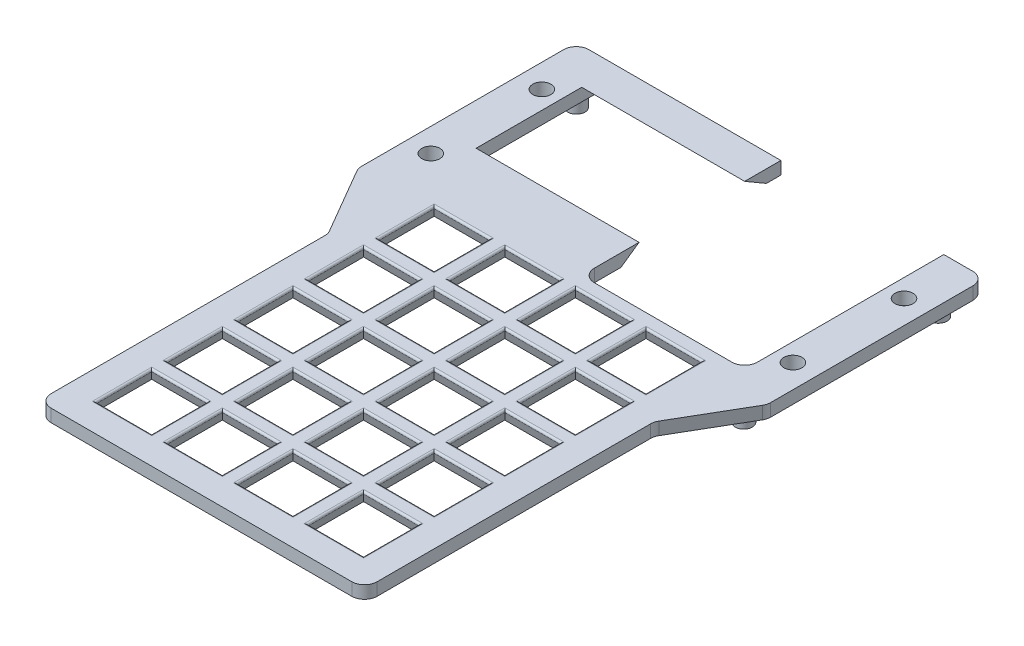
SolidWorks part; units mm, degrees
ref_plane "Front Plane" through (0, 0, 0) normal (0, 0, 1) x (1, 0, 0)
ref_plane "Top Plane" through (0, 0, 0) normal (0, 1, 0) x (1, 0, 0)
ref_plane "Right Plane" through (0, 0, 0) normal (1, 0, 0) x (0, 0, -1)
sketch "Sketch1" plane through (0, 0, 0) normal (0, 1, 0) x (1, 0, 0)
  line L0 (-57.5973, -8.4441) -> (-46.0973, -28.1941)
  line L1 (-46.0973, 51.8059) -> (43.9027, 51.8059)
  line L2 (-46.0973, 51.8059) -> (-46.0973, -108.1941)
  line L3 (-46.0973, -108.1941) -> (43.9027, -108.1941)
  line L4 (43.9027, 51.8059) -> (43.9027, -108.1941)
  line L5 (-57.5973, 51.8059) -> (55.4027, 51.8059)
  line L6 (-57.5973, 51.8059) -> (-57.5973, -8.4441)
  line L7 (-57.5973, -8.4441) -> (55.4027, -8.4441)
  line L8 (55.4027, 51.8059) -> (55.4027, -8.4441)
  line L9 (-57.5973, -8.4441) -> (-46.0973, -8.4441)
  line L10 (-46.0973, -8.4441) -> (-46.0973, -28.1941)
  line L11 (43.9027, -28.1941) -> (43.9027, -8.4441)
  line L12 (43.9027, -8.4441) -> (55.4027, -8.4441)
  line L13 (43.9027, -28.1941) -> (55.4027, -8.4441)
  point P12 (-1.0973, 51.8059)
  point P13 (-1.0973, 51.8059)
  dimension "D1" = 90
  dimension "D2" = 160
  dimension "D3" = 99.75
  dimension "D4" = 113
extrude "Boss-Extrude1" add sketch "Sketch1" along normal blind 3.5 contours L8 L5 L4 L7 | L2 L7 L4 L1 | L6 L7 L2 L5 | L7 L0 L2 | L7 L2 L3 L4 | L4 L13 L7
sketch "Sketch2" plane through (0, 0, 0) normal (0, -1, 0) x (1, 0, 0)
  line L2 (-46.0973, 28.1941) -> (-46.0973, 108.1941) construction
  line L3 (-57.5973, -51.8059) -> (55.4027, -51.8059) construction
  line L4 (-57.5973, -51.8059) -> (-57.5973, 8.4441) construction
  line L5 (55.4027, -51.8059) -> (55.4027, 8.4441) construction
  circle A2 centre (-51.0973, -45.3059) radius 2.4
  circle A3 centre (48.9027, -45.3059) radius 2.4
  circle A4 centre (-31.8473, -5.1309) radius 2.4
  circle A5 centre (-21.8473, -5.1309) radius 2.4
  circle A6 centre (47.4027, 6.9441) radius 2.35
  circle A7 centre (-49.5973, 6.9441) radius 2.35
  point P0 (0, 0)
  dimension "D5" = 4.8
  dimension "D6" = 4.8
  dimension "D12" = 4.8
  dimension "D13" = 4.8
  dimension "D16" = 21.25
  dimension "D18" = 4.7
  dimension "D19" = 4.7
  dimension "D2" = 8
  dimension "D3" = 21.25
  dimension "D4" = 8
  dimension "D7" = 6.5
  dimension "D8" = 6.5
  dimension "D9" = 6.5
  dimension "D10" = 6.5
  dimension "D11" = 10
  dimension "D14" = 14.25
  dimension "D15" = 46.675
extrude "Boss-Extrude2" add sketch "Sketch2" along normal blind 5.5
sketch "Sketch3" plane through (0, 0, 0) normal (0, -1, 0) x (1, 0, 0)
  line L0 (-57.5973, -51.8059) -> (-57.5973, 8.4441) construction
  line L1 (-57.5973, -51.8059) -> (55.4027, -51.8059) construction
  line L2 (55.4027, -51.8059) -> (55.4027, 8.4441) construction
  line L12 (-46.0973, -12.6458) -> (43.9027, -12.6458)
  line L13 (-46.0973, -12.6458) -> (-46.0973, -41.8059)
  line L14 (-46.0973, -41.8059) -> (43.9027, -41.8059)
  line L15 (43.9027, -12.6458) -> (43.9027, -41.8059)
  line L16 (43.9027, -12.6458) -> (-1.0973, -12.6458)
  line L17 (43.9027, -12.6458) -> (43.9027, 3.1941)
  line L18 (43.9027, 3.1941) -> (-1.0973, 3.1941)
  line L19 (-1.0973, -12.6458) -> (-1.0973, 3.1941)
  line L20 (-1.0973, -41.8059) -> (43.9027, -41.8059)
  line L21 (-1.0973, -41.8059) -> (-1.0973, -51.8059)
  line L22 (-1.0973, -51.8059) -> (43.9027, -51.8059)
  line L23 (43.9027, -41.8059) -> (43.9027, -51.8059)
  circle A0 centre (-51.0973, -35.8059) radius 2.5
  circle A1 centre (48.9027, -35.8059) radius 2.5
  circle A2 centre (-51.0973, -5.1309) radius 2.5
  circle A3 centre (48.9027, -5.1309) radius 2.5
  circle A5 centre (-21.8473, -5.1309) radius 2.4
  circle A6 centre (-21.8473, -5.1309) radius 2.4
  point P21 (0, 0)
  point P30 (-1.0973, -51.8059)
  point P31 (-1.0973, -41.8059)
  dimension "D3" = 5
  dimension "D9" = 5
  dimension "D10" = 5
  dimension "D11" = 5
  dimension "D1" = 6.5
  dimension "D2" = 16
  dimension "D4" = 6.5
  dimension "D5" = 16
  dimension "D6" = 6.5
  dimension "D7" = 6.5
  dimension "D13" = 45
  dimension "D18" = 90
  dimension "D19" = 45
  dimension "D16" = 0
extrude "Cut-Extrude1" cut sketch "Sketch3" against normal blind 5 contours L21 L20 L23 L22 | L13 L12 L15 L14 | L17 L16 L19 L18 | A0 | A2 | A3 | A1
sketch "Sketch4" plane through (0, 3.5, 0) normal (0, -1, 0) x (1, 0, 0)
  line L0 (-46.0973, 108.1941) -> (43.9027, 108.1941) construction
  line L1 (-37.8473, 100.1941) -> (-22.8473, 100.1941)
  line L2 (-37.8473, 100.1941) -> (-37.8473, 85.1941)
  line L3 (-37.8473, 85.1941) -> (-22.8473, 85.1941)
  line L4 (-22.8473, 100.1941) -> (-22.8473, 85.1941)
  line L5 (-46.0973, 28.1941) -> (-46.0973, 108.1941) construction
  line L6 (-18.3473, 85.1941) -> (-3.3473, 85.1941)
  line L7 (-18.3473, 85.1941) -> (-18.3473, 100.1941)
  line L8 (-18.3473, 100.1941) -> (-3.3473, 100.1941)
  line L9 (-3.3473, 85.1941) -> (-3.3473, 100.1941)
  line L10 (1.1527, 100.1941) -> (16.1527, 100.1941)
  line L11 (1.1527, 100.1941) -> (1.1527, 85.1941)
  line L12 (1.1527, 85.1941) -> (16.1527, 85.1941)
  line L13 (16.1527, 100.1941) -> (16.1527, 85.1941)
  line L14 (20.6527, 100.1941) -> (35.6527, 100.1941)
  line L15 (20.6527, 100.1941) -> (20.6527, 85.1941)
  line L16 (20.6527, 85.1941) -> (35.6527, 85.1941)
  line L17 (35.6527, 100.1941) -> (35.6527, 85.1941)
  line L19 (-18.3473, 41.6941) -> (-3.3473, 41.6941)
  line L20 (-18.3473, 41.6941) -> (-18.3473, 26.6941)
  line L21 (-37.8473, 80.6941) -> (-22.8473, 80.6941)
  line L22 (-37.8473, 80.6941) -> (-37.8473, 65.6941)
  line L23 (-37.8473, 65.6941) -> (-22.8473, 65.6941)
  line L24 (-22.8473, 80.6941) -> (-22.8473, 65.6941)
  line L25 (-18.3473, 80.6941) -> (-3.3473, 80.6941)
  line L26 (-18.3473, 80.6941) -> (-18.3473, 65.6941)
  line L27 (-18.3473, 65.6941) -> (-3.3473, 65.6941)
  line L28 (-3.3473, 80.6941) -> (-3.3473, 65.6941)
  line L29 (1.1527, 80.6941) -> (16.1527, 80.6941)
  line L30 (1.1527, 80.6941) -> (1.1527, 65.6941)
  line L31 (1.1527, 65.6941) -> (16.1527, 65.6941)
  line L32 (16.1527, 80.6941) -> (16.1527, 65.6941)
  line L33 (20.6527, 80.6941) -> (35.6527, 80.6941)
  line L34 (20.6527, 80.6941) -> (20.6527, 65.6941)
  line L35 (20.6527, 65.6941) -> (35.6527, 65.6941)
  line L36 (35.6527, 80.6941) -> (35.6527, 65.6941)
  line L37 (-37.8473, 61.1941) -> (-22.8473, 61.1941)
  line L38 (-37.8473, 61.1941) -> (-37.8473, 46.1941)
  line L39 (-37.8473, 46.1941) -> (-22.8473, 46.1941)
  line L40 (-22.8473, 61.1941) -> (-22.8473, 46.1941)
  line L41 (-18.3473, 61.1941) -> (-3.3473, 61.1941)
  line L42 (-18.3473, 61.1941) -> (-18.3473, 46.1941)
  line L43 (-18.3473, 46.1941) -> (-3.3473, 46.1941)
  line L44 (-3.3473, 61.1941) -> (-3.3473, 46.1941)
  line L45 (1.1527, 61.1941) -> (16.1527, 61.1941)
  line L46 (1.1527, 61.1941) -> (1.1527, 46.1941)
  line L47 (1.1527, 46.1941) -> (16.1527, 46.1941)
  line L48 (16.1527, 61.1941) -> (16.1527, 46.1941)
  line L49 (20.6527, 61.1941) -> (35.6527, 61.1941)
  line L50 (20.6527, 61.1941) -> (20.6527, 46.1941)
  line L51 (20.6527, 46.1941) -> (35.6527, 46.1941)
  line L52 (35.6527, 61.1941) -> (35.6527, 46.1941)
  line L53 (-37.8473, 41.6941) -> (-22.8473, 41.6941)
  line L54 (-37.8473, 41.6941) -> (-37.8473, 26.6941)
  line L55 (-37.8473, 26.6941) -> (-22.8473, 26.6941)
  line L56 (-22.8473, 41.6941) -> (-22.8473, 26.6941)
  line L57 (-18.3473, 26.6941) -> (-3.3473, 26.6941)
  line L58 (-3.3473, 41.6941) -> (-3.3473, 26.6941)
  line L59 (1.1527, 41.6941) -> (16.1527, 41.6941)
  line L60 (1.1527, 41.6941) -> (1.1527, 26.6941)
  line L61 (1.1527, 26.6941) -> (16.1527, 26.6941)
  line L62 (16.1527, 41.6941) -> (16.1527, 26.6941)
  line L63 (20.6527, 41.6941) -> (35.6527, 41.6941)
  line L64 (20.6527, 41.6941) -> (20.6527, 26.6941)
  line L65 (20.6527, 26.6941) -> (35.6527, 26.6941)
  line L66 (35.6527, 41.6941) -> (35.6527, 26.6941)
  line L67 (-37.8473, 22.1941) -> (-22.8473, 22.1941)
  line L68 (-37.8473, 22.1941) -> (-37.8473, 7.1941)
  line L69 (-37.8473, 7.1941) -> (-22.8473, 7.1941)
  line L70 (-22.8473, 22.1941) -> (-22.8473, 7.1941)
  line L71 (-18.3473, 22.1941) -> (-3.3473, 22.1941)
  line L72 (-18.3473, 22.1941) -> (-18.3473, 7.1941)
  line L73 (-18.3473, 7.1941) -> (-3.3473, 7.1941)
  line L74 (-3.3473, 22.1941) -> (-3.3473, 7.1941)
  line L75 (1.1527, 22.1941) -> (16.1527, 22.1941)
  line L76 (1.1527, 22.1941) -> (1.1527, 7.1941)
  line L77 (1.1527, 7.1941) -> (16.1527, 7.1941)
  line L78 (16.1527, 22.1941) -> (16.1527, 7.1941)
  line L79 (20.6527, 22.1941) -> (35.6527, 22.1941)
  line L80 (20.6527, 22.1941) -> (20.6527, 7.1941)
  line L81 (20.6527, 7.1941) -> (35.6527, 7.1941)
  line L82 (35.6527, 22.1941) -> (35.6527, 7.1941)
  dimension "D1" = 8
  dimension "D2" = 15
  dimension "D3" = 15
  dimension "D4" = 15
  dimension "D5" = 15
  dimension "D6" = 8
  dimension "D7" = 15
  dimension "D8" = 15
  dimension "D9" = 15
  dimension "D10" = 15
  dimension "D11" = 8
  dimension "D12" = 8
  dimension "D13" = 4.5
  dimension "D14" = 4.5
  dimension "D15" = 4.5
  dimension "D16" = 8.25
  dimension "D17" = 15
  dimension "D18" = 15
  dimension "D19" = 15
  dimension "D20" = 15
  dimension "D21" = 15
  dimension "D22" = 15
  dimension "D23" = 15
  dimension "D24" = 15
  dimension "D25" = 15
  dimension "D26" = 15
  dimension "D27" = 15
  dimension "D28" = 15
  dimension "D29" = 15
  dimension "D30" = 15
  dimension "D31" = 15
  dimension "D32" = 15
  dimension "D33" = 15
  dimension "D34" = 15
  dimension "D35" = 15
  dimension "D36" = 15
  dimension "D37" = 15
  dimension "D38" = 15
  dimension "D39" = 15
  dimension "D40" = 15
  dimension "D41" = 15
  dimension "D42" = 15
  dimension "D43" = 15
  dimension "D44" = 15
  dimension "D45" = 15
  dimension "D46" = 15
  dimension "D47" = 15
  dimension "D48" = 15
  dimension "D49" = 4.5
  dimension "D50" = 4.5
  dimension "D51" = 4.5
  dimension "D52" = 4.5
  dimension "D53" = 4.5
  dimension "D54" = 4.5
  dimension "D55" = 4.5
  dimension "D56" = 4.5
  dimension "D57" = 4.5
  dimension "D58" = 4.5
  dimension "D59" = 4.5
  dimension "D60" = 4.5
  dimension "D61" = 4.5
  dimension "D62" = 4.5
  dimension "D63" = 4.5
  dimension "D64" = 4.5
extrude "Cut-Extrude2" cut sketch "Sketch4" along normal up to surface (3.5 mm away) draft 20
fillet "Fillet1" radius 3.5 10 edges at (-57.5973, 1.75, 8.4441) (-46.0973, 1.75, 28.1941) (-46.0973, 1.75, 108.1941) (43.9027, 1.75, 108.1941) (43.9027, 1.75, 28.1941) (55.4027, 1.75, 8.4441) (55.4027, 1.75, -51.8059) (-57.5973, 1.75, -51.8059) (43.9027, 1.75, 3.1941) (-1.0973, 1.75, 3.1941)
fillet "Fillet3" radius 0.5 80 edges at (-37.8473, 3.5, 92.6941) (-30.3473, 3.5, 100.1941) (-30.3473, 3.5, 85.1941) (-22.8473, 3.5, 92.6941) (-18.3473, 3.5, 92.6941) (-10.8473, 3.5, 100.1941) (-10.8473, 3.5, 85.1941) (-3.3473, 3.5, 92.6941) (8.6527, 3.5, 100.1941) (1.1527, 3.5, 92.6941) (8.6527, 3.5, 85.1941) (16.1527, 3.5, 92.6941) (28.1527, 3.5, 100.1941) (35.6527, 3.5, 92.6941) (28.1527, 3.5, 85.1941) (20.6527, 3.5, 92.6941) (28.1527, 3.5, 80.6941) (35.6527, 3.5, 73.1941) (28.1527, 3.5, 65.6941) (20.6527, 3.5, 73.1941) (8.6527, 3.5, 65.6941) (1.1527, 3.5, 73.1941) (8.6527, 3.5, 80.6941) (16.1527, 3.5, 73.1941) (-3.3473, 3.5, 73.1941) (-10.8473, 3.5, 65.6941) (-10.8473, 3.5, 80.6941) (-18.3473, 3.5, 73.1941) (-30.3473, 3.5, 65.6941) (-22.8473, 3.5, 73.1941) (-30.3473, 3.5, 80.6941) (-37.8473, 3.5, 73.1941) (-30.3473, 3.5, 61.1941) (-22.8473, 3.5, 53.6941) (-30.3473, 3.5, 46.1941) (-37.8473, 3.5, 53.6941) (-10.8473, 3.5, 46.1941) (-18.3473, 3.5, 53.6941) (-10.8473, 3.5, 61.1941) (-3.3473, 3.5, 53.6941) (8.6527, 3.5, 46.1941) (1.1527, 3.5, 53.6941) (8.6527, 3.5, 61.1941) (16.1527, 3.5, 53.6941) (28.1527, 3.5, 46.1941) (20.6527, 3.5, 53.6941) (28.1527, 3.5, 61.1941) (35.6527, 3.5, 53.6941) (28.1527, 3.5, 26.6941) (20.6527, 3.5, 34.1941) (28.1527, 3.5, 41.6941) (35.6527, 3.5, 34.1941) (8.6527, 3.5, 26.6941) (16.1527, 3.5, 34.1941) (8.6527, 3.5, 41.6941) (1.1527, 3.5, 34.1941) (-10.8473, 3.5, 26.6941) (-3.3473, 3.5, 34.1941) (-10.8473, 3.5, 41.6941) (-18.3473, 3.5, 34.1941) (-37.8473, 3.5, 34.1941) (-30.3473, 3.5, 41.6941) (-30.3473, 3.5, 26.6941) (-22.8473, 3.5, 34.1941) (-30.3473, 3.5, 7.1941) (-37.8473, 3.5, 14.6941) (-30.3473, 3.5, 22.1941) (-22.8473, 3.5, 14.6941) (-10.8473, 3.5, 7.1941) (-3.3473, 3.5, 14.6941) (-10.8473, 3.5, 22.1941) (-18.3473, 3.5, 14.6941) (1.1527, 3.5, 14.6941) (8.6527, 3.5, 22.1941) (8.6527, 3.5, 7.1941) (16.1527, 3.5, 14.6941) (20.6527, 3.5, 14.6941) (28.1527, 3.5, 7.1941) (28.1527, 3.5, 22.1941) (35.6527, 3.5, 14.6941)
sketch "Sketch5" plane through (-1.0973, 0, 0) normal (1, 0, 0) x (0, 0, -1)
  line L0 (41.8059, 3.5) -> (47.8059, 0)
  line L1 (47.8059, 0) -> (41.8059, 0)
  line L2 (41.8059, 0) -> (41.8059, 3.5)
  line L3 (12.6458, 3.5) -> (7.6458, 0)
  line L4 (12.6458, 0) -> (0.3059, 0) construction
  line L5 (7.6458, 0) -> (12.6458, 0)
  line L6 (12.6458, 0) -> (12.6458, 3.5)
  line L7 (48.3059, 0) -> (-7.4994, 0) construction
  line L8 (42.9059, 0) -> (47.7059, 0) construction
  point P10 (7.4924, 0)
  point P15 (46.6381, 0)
  point P18 (8.122, 0)
  dimension "D1" = 5
  dimension "D2" = 6
extrude "Cut-Extrude3" cut sketch "Sketch5" against normal up to surface (45 mm away) up to face at (-46.0973, 1.75, -27.2258)
